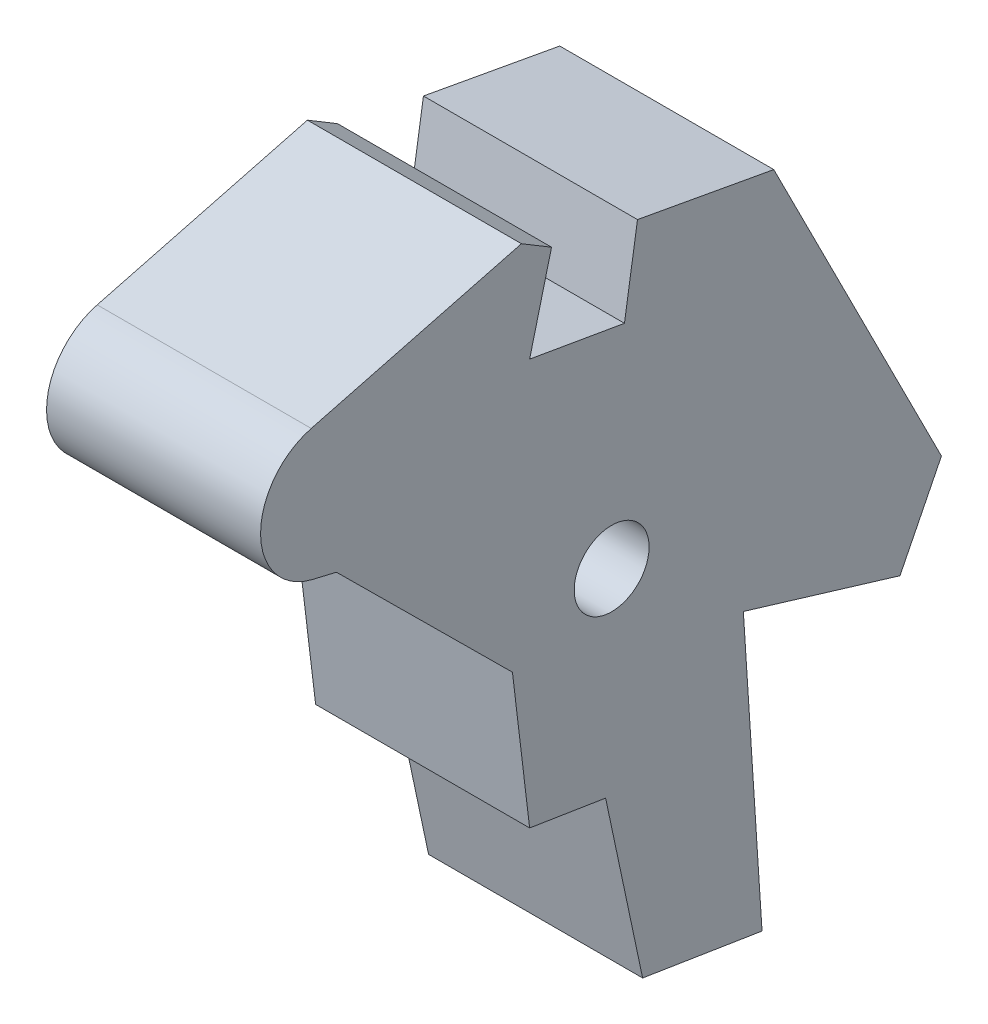
SolidWorks part; units mm, degrees
ref_plane "정면" through (0, 0, 0) normal (0, 0, 1) x (1, 0, 0)
ref_plane "윗면" through (0, 0, 0) normal (0, 1, 0) x (1, 0, 0)
ref_plane "우측면" through (0, 0, 0) normal (1, 0, 0) x (0, 0, -1)
sketch "스케치1" plane through (0, 0, 0) normal (1, 0, 0) x (0, 0, -1)
  line L0 (-16.8436, 15.2251) -> (-5.0583, 18.3019)
  line L1 (-16.7556, 7.8497) -> (-15.4326, 7.5378)
  line L2 (-5.5631, -2.251) -> (-4.5988, -10.2976)
  line L3 (-4.5988, -10.2976) -> (-0.3385, -10.9774)
  line L4 (-0.3385, -10.9774) -> (1.7372, -20.7507)
  line L5 (1.7372, -20.7507) -> (8.4318, -21.819)
  line L6 (8.4318, -21.819) -> (7.3833, -5.7778)
  line L7 (7.3833, -5.7778) -> (16.1657, -8.4329)
  line L8 (16.1657, -8.4329) -> (18.4908, -3.7828)
  line L10 (0.7188, 11.5483) -> (1.4481, 16.2201)
  line L11 (0.7188, 11.5483) -> (-4.5988, 12.4668)
  line L12 (-3.37, 17.2875) -> (-4.5988, 12.4668)
  line L13 (-3.37, 17.2875) -> (-5.0583, 18.3019)
  line L14 (-15.4326, 7.5378) -> (-5.5631, -2.251)
  line L15 (1.4481, 16.2201) -> (9.0902, 14.8272)
  line L16 (9.0902, 14.8272) -> (18.4908, -3.7828)
  circle A0 centre (0, 0) radius 2.1
  arc A1 (-16.8436, 15.2251) -> (-16.7556, 7.8497) centre (-15.8837, 11.5483) ccw
  dimension "D1" = 4.2
  dimension "D2" = 3.8
extrude "보스-돌출1" add sketch "스케치1" along normal mid plane 12
